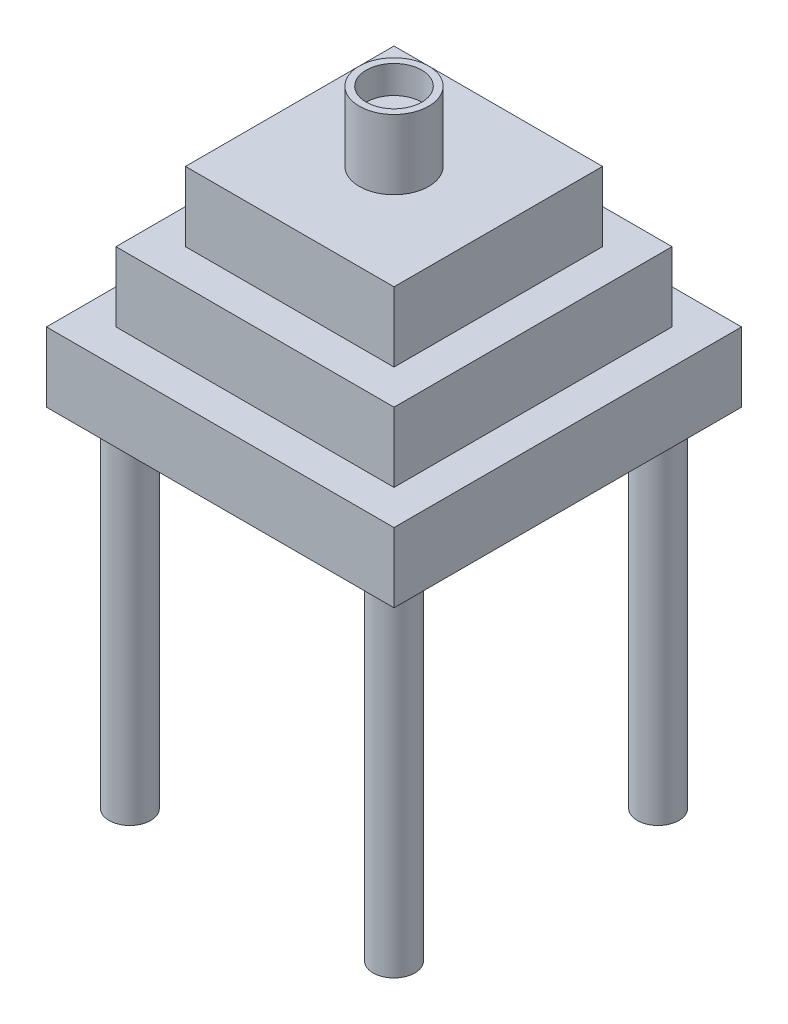
SolidWorks part; units mm, degrees
ref_plane "Front Plane" through (0, 0, 0) normal (0, 0, 1) x (1, 0, 0)
ref_plane "Top Plane" through (0, 0, 0) normal (0, 1, 0) x (1, 0, 0)
ref_plane "Right Plane" through (0, 0, 0) normal (1, 0, 0) x (0, 0, -1)
sketch "Sketch1" plane through (0, 0, 0) normal (0, 1, 0) x (1, 0, 0)
  line L0 (-190, -190) -> (-190, 190) construction
  line L1 (-190, -190) -> (190, -190) construction
  circle A0 centre (-190, -190) radius 30
  circle A1 centre (-190, 190) radius 30
  circle A2 centre (190, 190) radius 30
  circle A3 centre (190, -190) radius 30
  point P11 (0, 0)
  dimension "D2" = 60
  dimension "D3" = 380
  dimension "D1" = 4
extrude "Boss-Extrude1" add sketch "Sketch1" along normal blind 500
sketch "Sketch2" plane through (0, 500, 0) normal (0, 1, 0) x (1, 0, 0)
  line L1 (-250, -250) -> (250, -250)
  line L2 (-250, -250) -> (-250, 250)
  line L3 (-250, 250) -> (250, 250)
  line L4 (250, -250) -> (250, 250)
  line L5 (-250, -250) -> (250, 250) construction
  line L6 (-250, 250) -> (250, -250) construction
  point P0 (0, 0)
  dimension "D1" = 500
extrude "Boss-Extrude2" add sketch "Sketch2" along normal blind 100
sketch "Sketch3" plane through (0, 600, 0) normal (0, 1, 0) x (1, 0, 0)
  line L1 (-200, -200) -> (200, -200)
  line L2 (-200, -200) -> (-200, 200)
  line L3 (-200, 200) -> (200, 200)
  line L4 (200, -200) -> (200, 200)
  line L5 (-200, -200) -> (200, 200) construction
  line L6 (-200, 200) -> (200, -200) construction
  point P0 (0, 0)
  dimension "D1" = 400
extrude "Boss-Extrude3" add sketch "Sketch3" along normal blind 100
sketch "Sketch4" plane through (0, 700, 0) normal (0, 1, 0) x (1, 0, 0)
  line L1 (-150, -150) -> (150, -150)
  line L2 (-150, -150) -> (-150, 150)
  line L3 (-150, 150) -> (150, 150)
  line L4 (150, -150) -> (150, 150)
  line L5 (-150, -150) -> (150, 150) construction
  line L6 (-150, 150) -> (150, -150) construction
  point P0 (0, 0)
  dimension "D1" = 300
extrude "Boss-Extrude4" add sketch "Sketch4" along normal blind 100
sketch "Sketch5" plane through (0, 800, 0) normal (0, 1, 0) x (1, 0, 0)
  circle A0 centre (0, 0) radius 50
  dimension "D1" = 100
extrude "Boss-Extrude5" add sketch "Sketch5" along normal blind 100
sketch "Sketch6" plane through (0, 900, 0) normal (0, 1, 0) x (1, 0, 0)
  circle A0 centre (0, 0) radius 40
  circle A1 centre (0, 0) radius 50 construction
  dimension "D1" = 10
extrude "Cut-Extrude1" cut sketch "Sketch6" against normal blind 40
